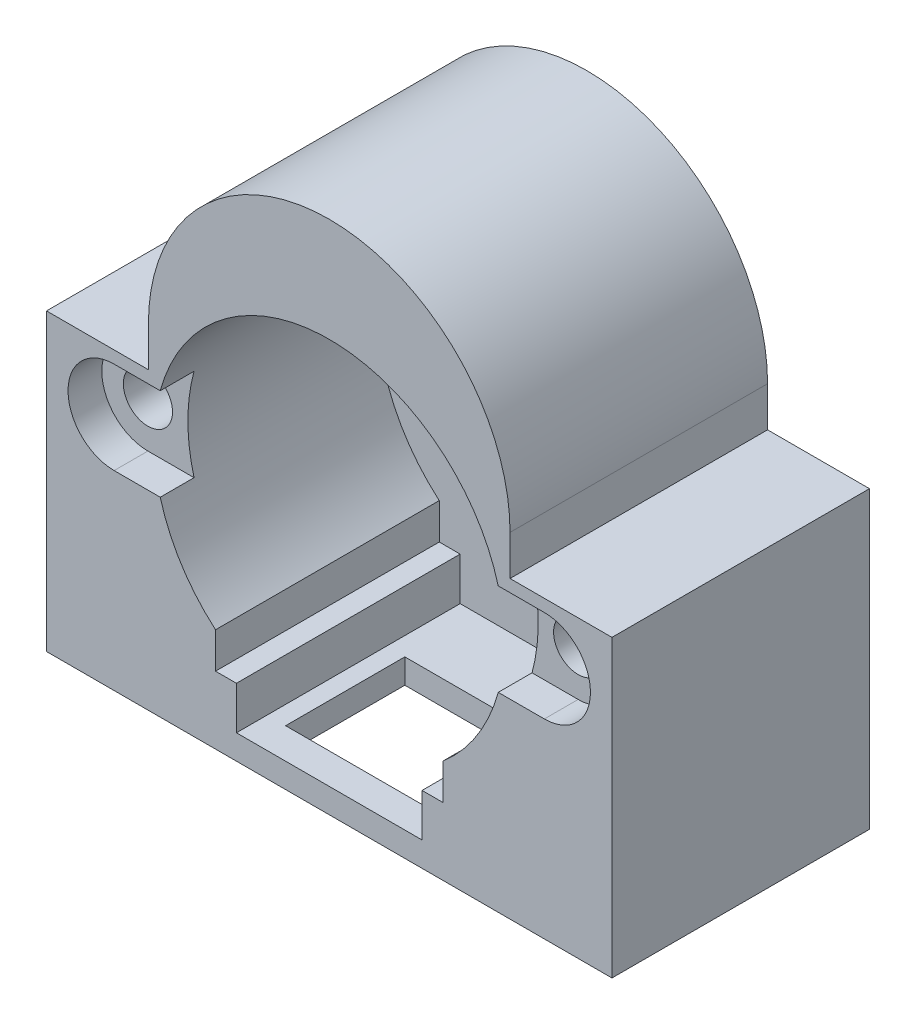
SolidWorks part; units mm, degrees
ref_plane "Front Plane" through (0, 0, 0) normal (0, 0, 1) x (1, 0, 0)
ref_plane "Top Plane" through (0, 0, 0) normal (0, 1, 0) x (1, 0, 0)
ref_plane "Right Plane" through (0, 0, 0) normal (1, 0, 0) x (0, 0, -1)
sketch "Sketch2" plane through (0, 0, 0) normal (0, 0, 1) x (1, 0, 0)
  line L0 (-7.55, -13.7589) -> (-7.55, -17.25)
  line L1 (-7.55, -17.25) -> (7.55, -17.25)
  line L2 (7.55, -17.25) -> (7.55, -13.7589)
  line L3 (7.55, -13.7589) -> (9.25, -13.7589)
  line L4 (9.25, -13.7589) -> (9.25, -10.8397)
  line L5 (-7.55, -13.7589) -> (-9.25, -13.7589)
  line L6 (-9.25, -13.7589) -> (-9.25, -10.8397)
  line L7 (-14.7095, 8) -> (-23, 8)
  line L8 (-23, 8) -> (-23, -19.25)
  line L10 (14.7095, 8) -> (23, 8)
  line L11 (23, 8) -> (23, -19.25)
  line L13 (-23, -19.25) -> (23, -19.25)
  arc A0 (14.7095, 8) -> (-14.7095, 8) centre (0, 8) ccw
  arc A4 (9.25, -10.8397) -> (-9.25, -10.8397) centre (0, 0) ccw
  point P6 (0, 0)
  point P11 (0, 0)
  point P15 (0, 0)
  point P16 (0, 8)
  point P17 (0, 0)
  point P18 (0, 0)
  dimension "D1" = 8.2905
  dimension "D12" = 3.4911
  dimension "D16" = 14.25
  dimension "D17" = 14.7095
  dimension "D2" = 8.2905
  dimension "D4" = 2
  dimension "D5" = 27.25
  dimension "D6" = 27.25
  dimension "D7" = 46
  dimension "D9" = 2.9191
  dimension "D10" = 1.7
  dimension "D11" = 1.7
  dimension "D13" = 15.1
  dimension "D14" = 2.9191
  dimension "D15" = 3.4911
extrude "Boss-Extrude1" add sketch "Sketch2" along normal blind 20.95
sketch "Sketch3" plane through (0, 0, 0) normal (0, 0, 1) x (1, 0, 0)
  line L7 (-14.7095, 8) -> (-23, 8)
  line L8 (-23, 8) -> (-23, -19.25)
  line L9 (14.7095, 8) -> (23, 8)
  line L10 (23, 8) -> (23, -19.25)
  line L11 (-23, -19.25) -> (23, -19.25)
  line L12 (23, 8) -> (14.7095, 8) construction
  line L13 (-23, 8) -> (-23, -19.25) construction
  line L17 (-23, -19.25) -> (23, -19.25) construction
  line L19 (23, -19.25) -> (23, 8) construction
  arc A0 (14.7095, 8) -> (-14.7095, 8) centre (0, 8) ccw
  arc A1 (14.7095, 8) -> (-14.7095, 8) centre (0, 8) ccw construction
  dimension "D1" = 0
extrude "Boss-Extrude2" add sketch "Sketch3" along normal blind 2.75
sketch "Sketch6" plane through (0, 0, 20.95) normal (0, 0, 1) x (1, 0, 0)
  line L0 (-14.7095, 8) -> (-23, 8) construction
  line L1 (-23, 8) -> (-23, -19.25) construction
  line L2 (23, 8) -> (14.7095, 8) construction
  line L3 (23, -19.25) -> (23, 8) construction
  circle A0 centre (-17.5, 0) radius 2
  circle A1 centre (17.5, 0) radius 2
  dimension "D1" = 8
  dimension "D2" = 5.5
  dimension "D3" = 4
  dimension "D4" = 8
  dimension "D5" = 5.5
  dimension "D6" = 4
extrude "Cut-Extrude2" cut sketch "Sketch6" against normal blind 10
sketch "Sketch7" plane through (0, 0, 20.95) normal (0, 0, 1) x (1, 0, 0)
  line L0 (-17.5, 0) -> (17.5, 0) construction
  line L3 (-17.5, 3.75) -> (17.5, 3.75)
  line L4 (-17.5, -3.75) -> (17.5, -3.75)
  arc A2 (-17.5, 3.75) -> (-17.5, -3.75) centre (-17.5, 0) ccw
  arc A3 (17.5, -3.75) -> (17.5, 3.75) centre (17.5, 0) ccw
  circle A4 centre (-17.5, 0) radius 2 construction
  circle A5 centre (-17.5, 0) radius 2 construction
  circle A6 centre (17.5, 0) radius 2 construction
  point P2 (0, 0)
  dimension "D2" = 7.5
  dimension "D3" = 1.75
  dimension "D4" = 1.75
  dimension "D1" = 3.75
extrude "Cut-Extrude3" cut sketch "Sketch7" against normal blind 2.75
sketch "Sketch8" plane through (0, 0, 20.95) normal (0, 0, 1) x (1, 0, 0)
  line L0 (-14.7095, 8) -> (-23, 8) construction
  line L1 (-14.7095, 8) -> (-23, 8)
  line L2 (-14.7095, 8) -> (-14.7095, 4.75)
  line L3 (-14.7095, 4.75) -> (-23, 4.75)
  line L4 (-23, 8) -> (-23, 4.75)
  line L5 (14.7095, 8) -> (23, 8)
  line L6 (14.7095, 8) -> (14.7095, 4.75)
  line L7 (14.7095, 4.75) -> (23, 4.75)
  line L8 (23, 8) -> (23, 4.75)
  line L9 (-23, 8) -> (-23, -19.25) construction
  line L10 (-13.7477, 3.75) -> (-17.5, 3.75) construction
  line L11 (17.5, 3.75) -> (13.7477, 3.75) construction
  line L12 (23, -19.25) -> (23, 8) construction
  line L13 (23, 8) -> (14.7095, 8) construction
  point P20 (0, 0)
  point P22 (0, 0)
  dimension "D2" = 1
  dimension "D3" = 1
extrude "Cut-Extrude4" cut sketch "Sketch8" along normal through all both and the other way through all
sketch "Sketch9" plane through (0, -19.25, -19.25) normal (0, 1, 0) x (-1, 0, 0)
  line L1 (-6.05, 37.7) -> (6.05, 37.7)
  line L2 (-6.05, 37.7) -> (-6.05, 28)
  line L3 (-6.05, 28) -> (6.05, 28)
  line L4 (6.05, 37.7) -> (6.05, 28)
  line L7 (23, 40.2) -> (-23, 40.2) construction
  line L8 (-7.55, 40.2) -> (-7.55, 22) construction
  line L9 (7.55, 40.2) -> (7.55, 22) construction
  line L10 (7.55, 22) -> (-7.55, 22) construction
  dimension "D1" = 2.5
  dimension "D2" = 1.5
  dimension "D3" = 1.5
  dimension "D4" = 6
extrude "Cut-Extrude5" cut sketch "Sketch9" along normal up to next
